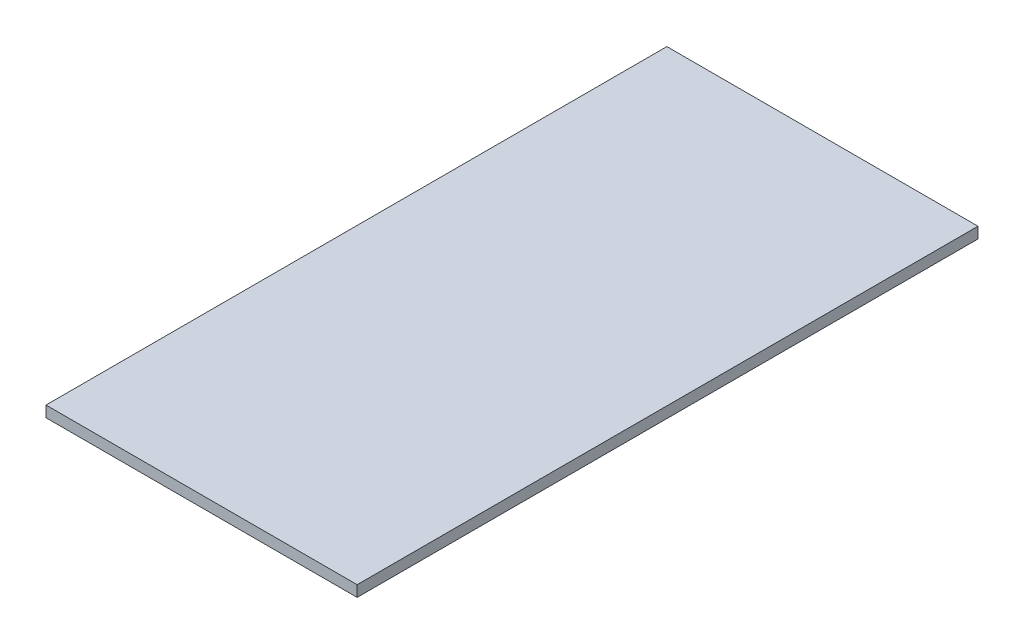
SolidWorks part; units mm, degrees
ref_plane "Alzado" through (0, 0, 0) normal (0, 0, 1) x (1, 0, 0)
ref_plane "Planta" through (0, 0, 0) normal (0, 1, 0) x (1, 0, 0)
ref_plane "Vista lateral" through (0, 0, 0) normal (1, 0, 0) x (0, 0, -1)
sketch "Croquis1" plane through (0, 224.7071, 0) normal (0, 1, 0) x (1, 0, 0)
  line L0 (80.653, -490) -> (80.653, -40) construction
  line L1 (-144.857, -490) -> (-144.857, -40) construction
  line L2 (80.653, -490) -> (80.653, -40) construction
  line L3 (-144.857, -490) -> (-144.857, -40) construction
  line L5 (-144.857, -40) -> (80.653, -40)
  line L6 (-144.857, -40) -> (-144.857, -490)
  line L7 (-144.857, -490) -> (80.653, -490)
  line L8 (80.653, -40) -> (80.653, -490)
extrude "Saliente-Extruir1" add sketch "Croquis1" along normal mid plane 8
